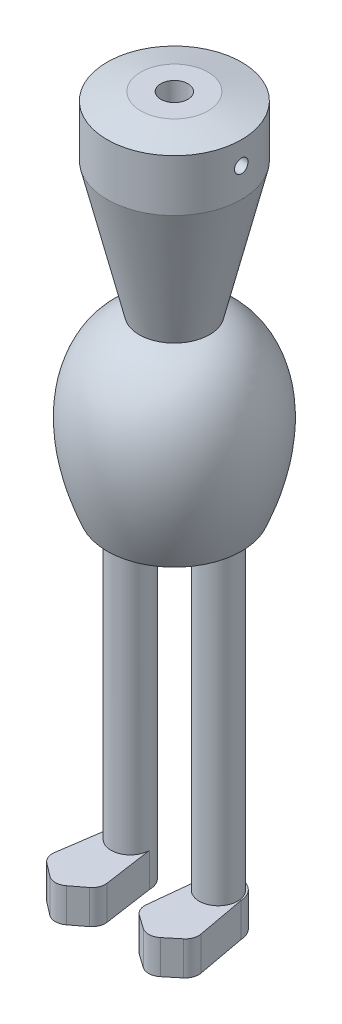
SolidWorks part; units mm, degrees
ref_plane "Front Plane" through (0, 0, 0) normal (0, 0, 1) x (1, 0, 0)
ref_plane "Top Plane" through (0, 0, 0) normal (0, 1, 0) x (1, 0, 0)
ref_plane "Right Plane" through (0, 0, 0) normal (1, 0, 0) x (0, 0, -1)
sketch "Sketch1" plane through (0, 0, 0) normal (0, 0, 1) x (1, 0, 0)
  line L0 (0, 53.6546) -> (0, -62.9305) construction
  line L1 (-5.1836, 0) -> (5.1836, 0)
  line L2 (5.1836, 0) -> (9.9125, 19.6431)
  line L3 (9.9125, 19.6431) -> (9.9125, 27.282)
  line L4 (9.9125, 27.282) -> (4.9562, 28.4752)
  line L5 (4.9562, -25.2813) -> (0, -25.2813)
  line L15 (-4.9562, -25.2813) -> (0, -25.2813)
  line L16 (-9.9125, 27.282) -> (-4.9562, 28.4752)
  line L17 (-9.9125, 19.6431) -> (-9.9125, 27.282)
  line L18 (-5.1836, 0) -> (-9.9125, 19.6431)
  line L20 (-9.9125, -25.2813) -> (-4.9562, -25.2813)
  line L21 (4.9562, -25.2813) -> (9.9125, -25.2813)
  line L22 (-4.9562, 28.4752) -> (4.9562, 28.4752)
  spline S0 degree 3 poles (5.1836, 0) (8.574, -1.1889) (14.4922, -9.3926) (12.1772, -19.841) (9.9125, -25.2813) knots 0 0 0 0 0.353823 1 1 1 1
  spline S5 degree 3 poles (-5.1836, 0) (-8.574, -1.1889) (-14.4922, -9.3926) (-12.1772, -19.841) (-9.9125, -25.2813) knots 0 0 0 0 0.353823 1 1 1 1
revolve "Revolve7" add sketch "Sketch1" angle 360 about L0
sketch "Sketch2" plane through (0, -25.2813, 0) normal (0, -1, 0) x (1, 0, 0)
  line L0 (0, 7.5513) -> (0, -7.3596) construction
  circle A0 centre (-6.4971, 0) radius 2.8337
  circle A1 centre (6.4971, 0) radius 2.8337
extrude "Boss-Extrude1" add sketch "Sketch2" along normal blind 45
sketch "Sketch3" plane through (0, -70.2813, 0) normal (0, -1, 0) x (1, 0, 0)
  line L0 (-9.3308, 0) -> (-10.5603, 8.4712)
  line L1 (-10.5603, 8.4712) -> (-6.4971, 11.576)
  line L2 (-6.4971, 14.7192) -> (-6.4971, -4.4081) construction
  line L3 (-3.6635, 0) -> (-2.434, 8.4712)
  line L4 (-2.434, 8.4712) -> (-6.4971, 11.576)
  line L5 (0.3641, 14.7192) -> (0, -3.9864) construction
  line L6 (2.917, 8.367) -> (7.0979, 11.3114)
  line L7 (3.8159, -0.1456) -> (2.917, 8.367)
  line L8 (11.0371, 8.0508) -> (7.0979, 11.3114)
  line L9 (9.4789, -0.3662) -> (11.0371, 8.0508)
  circle A0 centre (-6.4971, 0) radius 2.8337 construction
  circle A1 centre (-6.4971, 0) radius 2.8337 construction
  arc A2 (-9.3308, 0) -> (-3.6635, 0) centre (-6.4971, 0) ccw
  arc A3 (9.4789, -0.3662) -> (3.8159, -0.1456) centre (6.6474, -0.2559) cw
extrude "Boss-Extrude2" add sketch "Sketch3" along normal blind 5
fillet "Fillet1" radius 2 2 edges at (7.0979, -72.7813, 11.3114) (-6.4971, -72.7813, 11.576)
fillet "Fillet2" radius 2 4 edges at (11.0371, -72.7813, 8.0508) (2.917, -72.7813, 8.367) (-10.5603, -72.7813, 8.4712) (-2.434, -72.7813, 8.4712)
sketch "Sketch5" plane through (0, 0, 0) normal (1, 0, 0) x (0, 0, -1)
  circle A0 centre (0, 23.9363) radius 1
extrude "Cut-Extrude2" cut sketch "Sketch5" against normal blind 96 and the other way blind 115
sketch "Sketch6" plane through (0, 0, 0) normal (0, 0, 1) x (1, 0, 0)
  circle A0 centre (0, 23.79) radius 0.9982
  circle A1 centre (0, 10.29) radius 1
sketch "Sketch8" plane through (0, 28.4752, 0) normal (0, 1, 0) x (1, 0, 0)
  circle A0 centre (0, 0) radius 2
extrude "Cut-Extrude3" cut sketch "Sketch8" against normal blind 93
